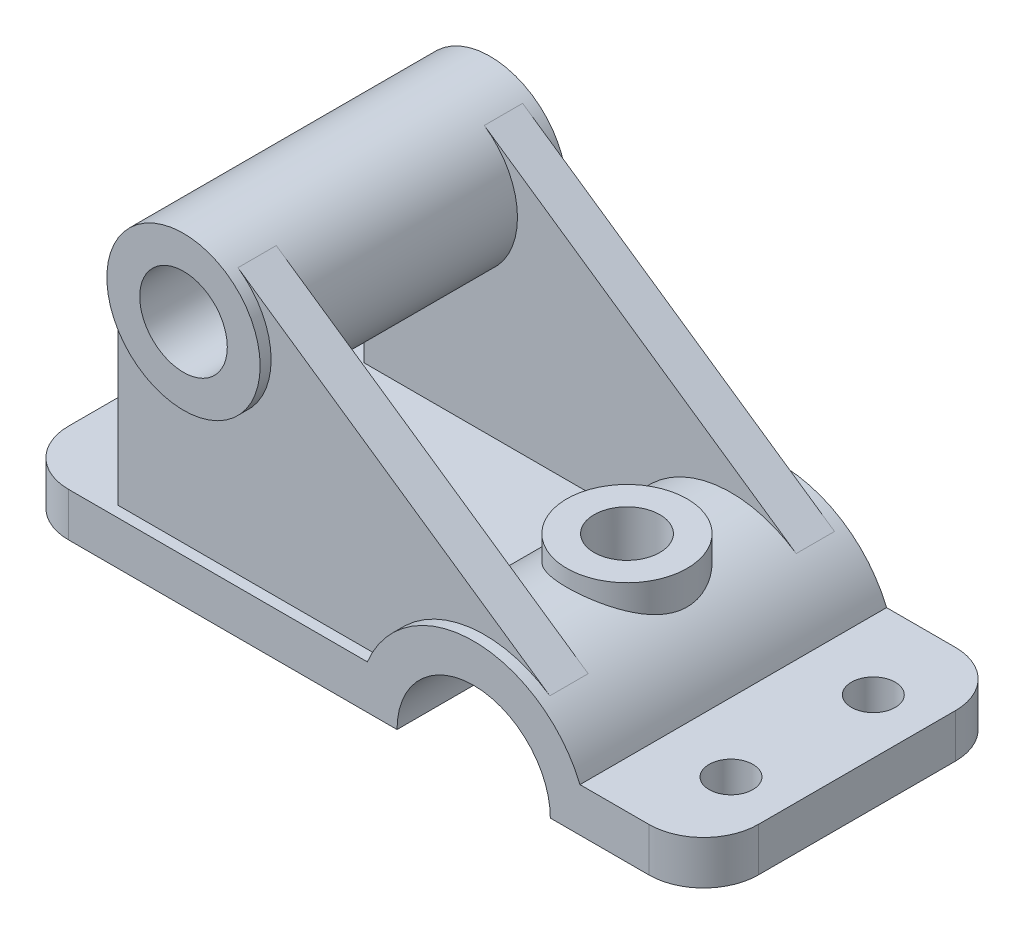
SolidWorks part; units mm, degrees
ref_plane "Front Plane" through (0, 0, 0) normal (0, 0, 1) x (1, 0, 0)
ref_plane "Top Plane" through (0, 0, 0) normal (0, 1, 0) x (1, 0, 0)
ref_plane "Right Plane" through (0, 0, 0) normal (1, 0, 0) x (0, 0, -1)
sketch "Sketch1" plane through (0, 0, 0) normal (0, 0, 1) x (1, 0, 0)
  line L0 (84, 8) -> (84, 0) construction
  line L1 (0, 0) -> (70, 0)
  line L2 (0, 0) -> (0, 8)
  line L3 (0, 8) -> (64.5835, 8)
  line L4 (126, 0) -> (126, 8)
  line L5 (98, 0) -> (126, 0)
  line L6 (103.4165, 8) -> (126, 8)
  arc A0 (103.4165, 8) -> (64.5835, 8) centre (84, 0) ccw
  arc A1 (98, 0) -> (70, 0) centre (84, 0) ccw
  dimension "D4" = 28
  dimension "D5" = 42
  dimension "D1" = 8
  dimension "D2" = 126
  dimension "D3" = 42
extrude "Boss-Extrude1" add sketch "Sketch1" along normal blind 56
fillet "Fillet1" radius 10 4 edges at (126, 4, 0) (126, 4, 56) (0, 4, 0) (0, 4, 56)
sketch "Sketch2" plane through (0, 8, 0) normal (0, 1, 0) x (1, 0, 0)
  line L0 (0, -28) -> (126, -28) construction
  line L1 (0, -46) -> (0, -10) construction
  line L2 (126, -46) -> (126, -10) construction
  circle A0 centre (10, -15) radius 4
  circle A1 centre (10, -41) radius 4
  circle A2 centre (116, -15) radius 4
  circle A3 centre (116, -41) radius 4
  dimension "D1" = 8
  dimension "D2" = 8
  dimension "D3" = 8
  dimension "D4" = 8
  dimension "D5" = 13
  dimension "D6" = 26
  dimension "D7" = 10
  dimension "D8" = 10
extrude "Cut-Extrude1" cut sketch "Sketch2" against normal blind 56
ref_plane "Plane1" through (0, 14, 0) normal (0, -1, 0) x (-1, 0, 0)
sketch "Sketch4" plane through (0, 14, 0) normal (0, -1, 0) x (-1, 0, 0)
  line L0 (0, -28) -> (-126, -28) construction
  line L1 (0, -46) -> (0, -10) construction
  line L2 (-126, -46) -> (-126, -10) construction
  line L3 (-84, 0) -> (-84, -56) construction
  line L4 (-64.5835, 0) -> (-103.4165, 0) construction
  line L5 (-103.4165, -56) -> (-64.5835, -56) construction
  circle A0 centre (-84, -28) radius 11
  circle A1 centre (-84, -28) radius 6
  dimension "D1" = 22
  dimension "D2" = 12
extrude "Boss-Extrude2" add sketch "Sketch4" against normal blind 10
sketch "Sketch5" plane through (0, 24, 0) normal (0, 1, 0) x (1, 0, 0)
  circle A0 centre (84, -28) radius 6
  dimension "D1" = 12
extrude "Cut-Extrude2" cut sketch "Sketch5" against normal blind 34
sketch "Sketch6" plane through (0, 0, 0) normal (0, 0, 1) x (1, 0, 0)
  line L0 (0, 0) -> (10, 0) construction
  circle A0 centre (31, 45) radius 14
  circle A1 centre (31, 45) radius 8
  dimension "D1" = 16
  dimension "D2" = 28
  dimension "D3" = 45
  dimension "D4" = 95
extrude "Boss-Extrude3" add sketch "Sketch6" along normal blind 56 separate body
ref_plane "Plane2" through (0, 0, 54) normal (0, 0, 1) x (1, 0, 0)
sketch "Sketch7" plane through (0, 0, 54) normal (0, 0, 1) x (1, 0, 0)
  line L0 (17, 45) -> (17, 8)
  line L1 (64.5835, 8) -> (10, 8) construction
  line L2 (17, 8) -> (64.5835, 8)
  line L3 (38.9407, 56.5302) -> (95.9111, 17.2953)
  circle A0 centre (31, 45) radius 14 construction
  arc A3 (103.4165, 8) -> (64.5835, 8) centre (84, 0) ccw construction
  arc A4 (17, 45) -> (38.9407, 56.5302) centre (31, 45) ccw
  arc A5 (64.5835, 8) -> (95.9111, 17.2953) centre (84, 0) cw
extrude "Boss-Extrude4" add sketch "Sketch7" against normal blind 7
ref_plane "Plane3" through (0, 0, 2) normal (0, 0, -1) x (-1, 0, 0)
sketch "Sketch8" plane through (0, 0, 2) normal (0, 0, -1) x (-1, 0, 0)
  line L0 (-17, 45) -> (-17, 8)
  line L1 (-17, 45) -> (-17, 8) construction
  line L2 (-17, 8) -> (-64.5835, 8)
  line L3 (-38.9407, 56.5302) -> (-95.9111, 17.2953)
  circle A0 centre (-31, 45) radius 14 construction
  arc A1 (-95.9111, 17.2953) -> (-64.5835, 8) centre (-84, 0) cw
  arc A2 (-38.9407, 56.5302) -> (-17, 45) centre (-31, 45) ccw
extrude "Boss-Extrude5" add sketch "Sketch8" against normal blind 7
